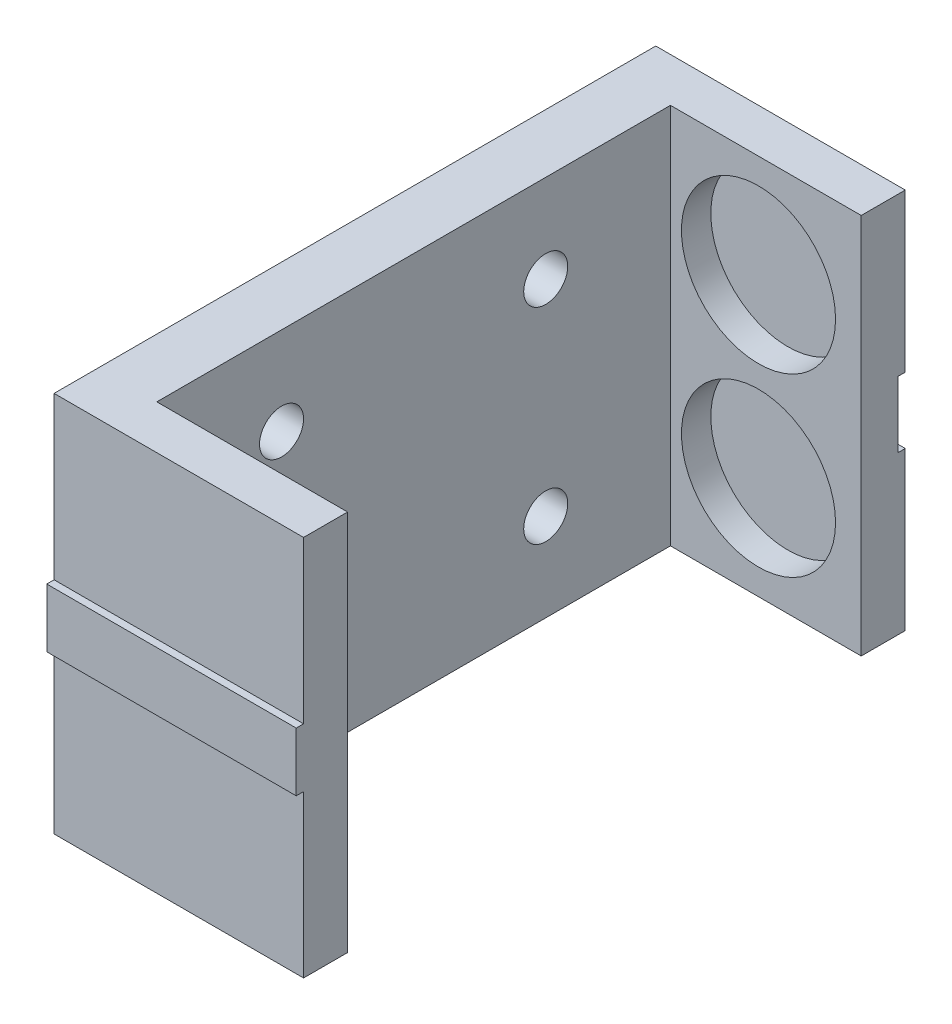
SolidWorks part; units mm, degrees
ref_plane "Plan de face" through (0, 0, 0) normal (0, 0, 1) x (1, 0, 0)
ref_plane "Plan de dessus" through (0, 0, 0) normal (0, 1, 0) x (1, 0, 0)
ref_plane "Plan de droite" through (0, 0, 0) normal (1, 0, 0) x (0, 0, -1)
sketch "Esquisse1" plane through (0, 0, 0) normal (0, 0, 1) x (1, 0, 0)
  line L1 (0, 0) -> (17, 0)
  line L2 (0, 0) -> (0, 26)
  line L3 (0, 26) -> (17, 26)
  line L4 (17, 0) -> (17, 26)
  dimension "D1" = 17
  dimension "D2" = 26
extrude "Boss.-Extru.1" add sketch "Esquisse1" along normal blind 3
sketch "Esquisse3" plane through (0, 0, 0) normal (0, 0, -1) x (-1, 0, 0)
  line L0 (0, 0) -> (-17, 0) construction
  line L1 (0, 26) -> (-4, 26)
  line L2 (0, 26) -> (0, 0)
  line L3 (0, 0) -> (-4, 0)
  line L4 (-4, 26) -> (-4, 0)
  dimension "D1" = 4
extrude "Boss.-Extru.2" add sketch "Esquisse3" along normal blind 38
sketch "Esquisse4" plane through (0, 0, 0) normal (-1, 0, 0) x (0, 0, 1)
  line L0 (3, 26) -> (-38, 26) construction
  line L1 (3, 0) -> (-38, 0) construction
  line L2 (3, 26) -> (3, 0) construction
  circle A0 centre (-8.5, 20) radius 1.5
  circle A1 centre (-8.5, 6) radius 1.5
  dimension "D1" = 3
  dimension "D2" = 3
  dimension "D3" = 6
  dimension "D4" = 6
  dimension "D5" = 11.5
  dimension "D6" = 11.5
extrude "Enlèv. mat.-Extru.2" cut sketch "Esquisse4" against normal blind 4
sketch "Esquisse5" plane through (0, 0, 0) normal (-1, 0, 0) x (0, 0, 1)
  line L0 (3, 26) -> (-38, 26) construction
  line L1 (3, 0) -> (-38, 0) construction
  line L2 (-38, 0) -> (-38, 26) construction
  circle A0 centre (-26.5, 19.9995) radius 1.5
  circle A1 centre (-26.5, 6) radius 1.5
  dimension "D5" = 3
  dimension "D6" = 3
  dimension "D1" = 6.0005
  dimension "D2" = 6
  dimension "D3" = 11.5
  dimension "D4" = 11.5
extrude "Enlèv. mat.-Extru.3" cut sketch "Esquisse5" against normal blind 4
sketch "Esquisse6" plane through (4, 0, 0) normal (1, 0, 0) x (0, 0, -1)
  line L0 (38, 26) -> (0, 26) construction
  line L1 (38, 0) -> (35, 0)
  line L2 (38, 0) -> (38, 26)
  line L3 (38, 26) -> (35, 26)
  line L4 (35, 0) -> (35, 26)
  dimension "D1" = 3
extrude "Boss.-Extru.3" add sketch "Esquisse6" along normal blind 13
sketch "Esquisse8" plane through (0, 0, 0) normal (0, 0, -1) x (-1, 0, 0)
  line L0 (-4, 0) -> (-17, 0) construction
  line L1 (-17, 0) -> (-17, 26) construction
  line L2 (-17, 26) -> (-4, 26) construction
  circle A0 centre (-10, 7) radius 5.25
  circle A1 centre (-10, 19) radius 5.25
  dimension "D1" = 10.5
  dimension "D2" = 10.5
  dimension "D3" = 7
  dimension "D4" = 7
  dimension "D5" = 7
  dimension "D6" = 7
extrude "Enlèv. mat.-Extru.4" cut sketch "Esquisse8" against normal blind 2
sketch "Esquisse9" plane through (0, 0, -35) normal (0, 0, 1) x (1, 0, 0)
  line L0 (17, 26) -> (17, 0) construction
  line L1 (17, 26) -> (4, 26) construction
  line L2 (17, 0) -> (4, 0) construction
  circle A0 centre (10, 19) radius 5.25
  circle A1 centre (10, 7) radius 5.25
  dimension "D1" = 10.5
  dimension "D2" = 10.5
  dimension "D3" = 7
  dimension "D4" = 7
  dimension "D5" = 7
  dimension "D6" = 7
extrude "Enlèv. mat.-Extru.5" cut sketch "Esquisse9" against normal blind 2
sketch "Esquisse10" plane through (0, 0, 3) normal (0, 0, 1) x (1, 0, 0)
  line L0 (0, 26) -> (0, 0) construction
  line L1 (0, 11) -> (17, 11)
  line L2 (0, 11) -> (0, 15)
  line L3 (0, 15) -> (17, 15)
  line L4 (17, 11) -> (17, 15)
  line L5 (17, 0) -> (17, 26) construction
  line L6 (17, 26) -> (0, 26) construction
  line L7 (0, 0) -> (17, 0) construction
  dimension "D1" = 11
  dimension "D2" = 11
  dimension "D3" = 4
extrude "Boss.-Extru.5" add sketch "Esquisse10" along normal blind 0.5
sketch "Esquisse11" plane through (0, 0, -38) normal (0, 0, -1) x (-1, 0, 0)
  line L0 (-17, 0) -> (-17, 26) construction
  line L1 (-17, 15.25) -> (0, 15.25)
  line L2 (-17, 15.25) -> (-17, 10.75)
  line L3 (-17, 10.75) -> (0, 10.75)
  line L4 (0, 15.25) -> (0, 10.75)
  line L5 (0, 0) -> (0, 26) construction
  line L6 (0, 26) -> (-17, 26) construction
  line L7 (-17, 0) -> (0, 0) construction
  dimension "D1" = 10.75
  dimension "D2" = 10.75
  dimension "D3" = 4.5
extrude "Enlèv. mat.-Extru.6" cut sketch "Esquisse11" against normal blind 0.5
